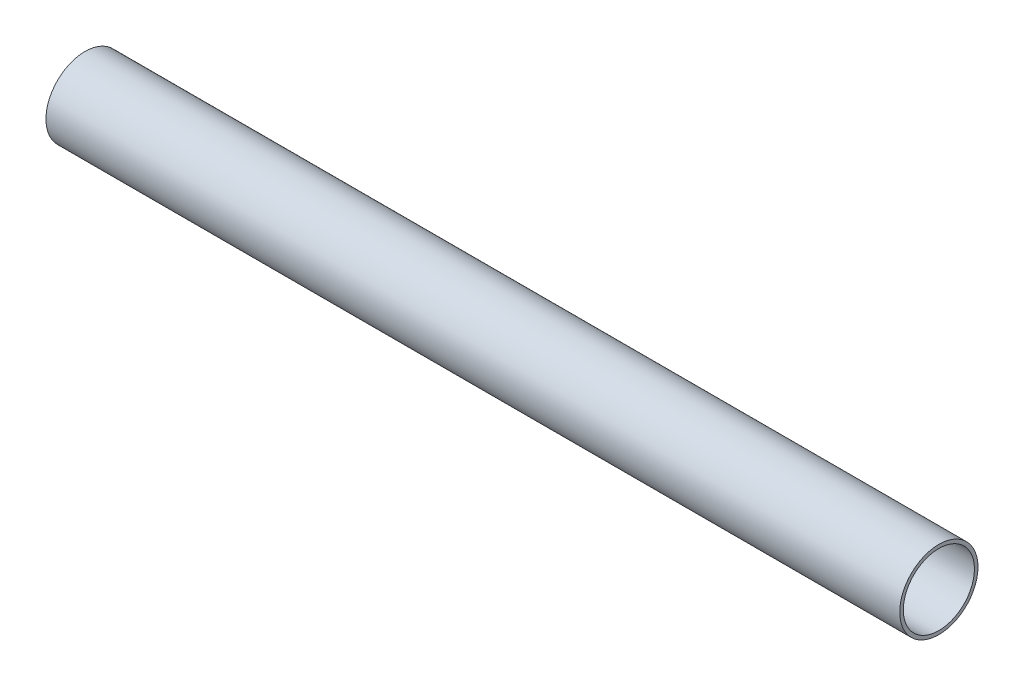
SolidWorks part; units mm, degrees
ref_plane "Front Plane" through (0, 0, 0) normal (0, 0, 1) x (1, 0, 0)
ref_plane "Top Plane" through (0, 0, 0) normal (0, 1, 0) x (1, 0, 0)
ref_plane "Right Plane" through (0, 0, 0) normal (1, 0, 0) x (0, 0, -1)
sketch "Sketch1" plane through (0, 0, 0) normal (1, 0, 0) x (0, 0, -1)
  circle A0 centre (0, 0) radius 31.75
  circle A1 centre (0, 0) radius 34.925
  dimension "D1" = 63.5
  dimension "D2" = 3.175
extrude "Boss-Extrude1" add sketch "Sketch1" along normal blind 762
